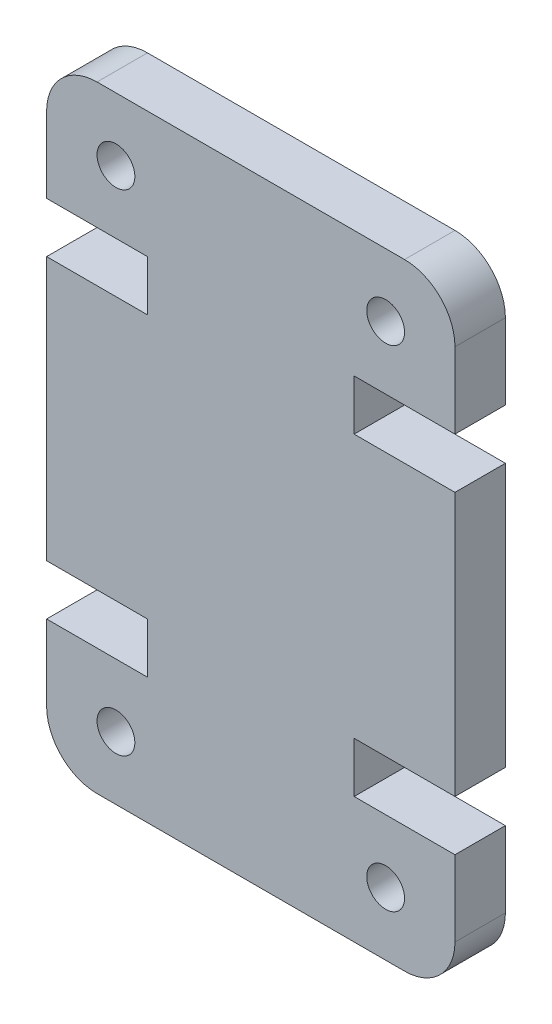
SolidWorks part; units mm, degrees
ref_plane "Front Plane" through (0, 0, 0) normal (0, 0, 1) x (1, 0, 0)
ref_plane "Top Plane" through (0, 0, 0) normal (0, 1, 0) x (1, 0, 0)
ref_plane "Right Plane" through (0, 0, 0) normal (1, 0, 0) x (0, 0, -1)
sketch "Sketch1" plane through (0, 0, 0) normal (0, 0, 1) x (1, 0, 0)
  line L0 (0, 17.45) -> (0, 7)
  line L1 (16.2, 5) -> (16.2, 2)
  line L2 (12.2, 5) -> (16.2, 5)
  line L3 (2, 0) -> (14.2, 0)
  line L4 (16.2, 7) -> (12.2, 7)
  line L5 (12.2, 7) -> (12.2, 5)
  line L6 (16.2, 17.45) -> (16.2, 7)
  line L7 (0, 19.45) -> (0, 22.45)
  line L8 (4, 19.45) -> (0, 19.45)
  line L9 (0, 17.45) -> (4, 17.45)
  line L10 (4, 7) -> (4, 5)
  line L11 (4, 17.45) -> (4, 19.45)
  line L12 (0, 7) -> (4, 7)
  line L13 (4, 5) -> (0, 5)
  line L14 (12.2, 17.45) -> (12.2, 19.45)
  line L15 (16.2, 17.45) -> (12.2, 17.45)
  line L16 (2, 24.45) -> (14.2, 24.45)
  line L17 (12.2, 19.45) -> (16.2, 19.45)
  line L18 (16.2, 19.45) -> (16.2, 22.45)
  line L19 (0, 5) -> (0, 2)
  line L20 (0, 12.225) -> (16.2, 12.225) construction
  line L21 (8.1, 24.45) -> (8.1, 0) construction
  circle A0 centre (13.45, 2.5) radius 0.75
  arc A1 (16.2, 2) -> (14.2, 0) centre (14.2, 2) cw
  circle A2 centre (2.75, 21.95) radius 0.75
  arc A3 (0, 2) -> (2, 0) centre (2, 2) ccw
  arc A4 (0, 22.45) -> (2, 24.45) centre (2, 22.45) cw
  circle A5 centre (2.75, 2.5) radius 0.75
  arc A6 (16.2, 22.45) -> (14.2, 24.45) centre (14.2, 22.45) ccw
  circle A7 centre (13.45, 21.95) radius 0.75
  point P17 (8.1, 12.225)
  dimension "D1" = 1.5
  dimension "D2" = 2
  dimension "D3" = 2.75
  dimension "D4" = 8.1
  dimension "D5" = 2.5
  dimension "D6" = 5
  dimension "D8" = 12.225
extrude "Boss-Extrude1" add sketch "Sketch1" along normal blind 4
sketch "Sketch2" plane through (0, 0, 0) normal (0, 0, -1) x (-1, 0, 0)
  line L0 (0, 0) -> (0, 24.45)
  line L1 (0, 24.45) -> (-16.2, 24.45)
  line L2 (-16.2, 24.45) -> (-16.2, 0)
  line L3 (-16.2, 0) -> (0, 0)
extrude "Cut-Extrude1" cut sketch "Sketch2" against normal blind 2
equation "\"D4@Sketch1\"= \"fingerWidth@parametersSketch@prostheticParameters.SLDPRT\" / 2 'MIP Width"
equation "\"D8@Sketch1\"= ( ( \"HL@parametersSketch@prostheticParameters.SLDPRT\" * 0.17 ) - 4 - 3 ) / 2 'MIP Length - Sil. Sht MIP - Sil. Sht DIP"
